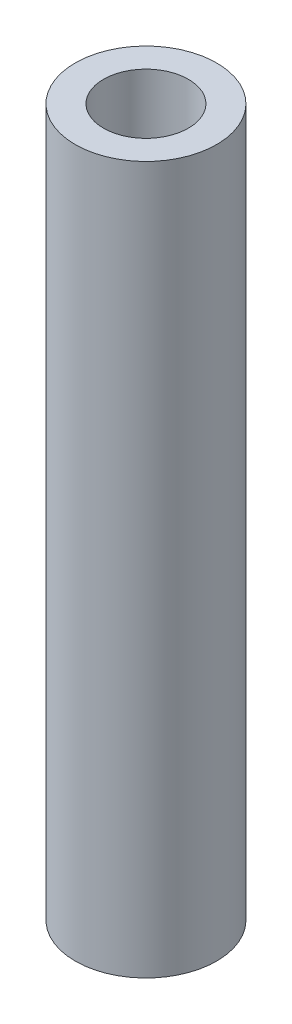
SolidWorks part; units mm, degrees
ref_plane "Front Plane" through (0, 0, 0) normal (0, 0, 1) x (1, 0, 0)
ref_plane "Top Plane" through (0, 0, 0) normal (0, 1, 0) x (1, 0, 0)
ref_plane "Right Plane" through (0, 0, 0) normal (1, 0, 0) x (0, 0, -1)
sketch "Sketch1" plane through (0, 0, 0) normal (0, 1, 0) x (1, 0, 0)
  circle A0 centre (0, 0) radius 3
  circle A1 centre (0, 0) radius 5
  dimension "D1" = 6
  dimension "D2" = 10
extrude "Boss-Extrude1" add sketch "Sketch1" along normal blind 50
